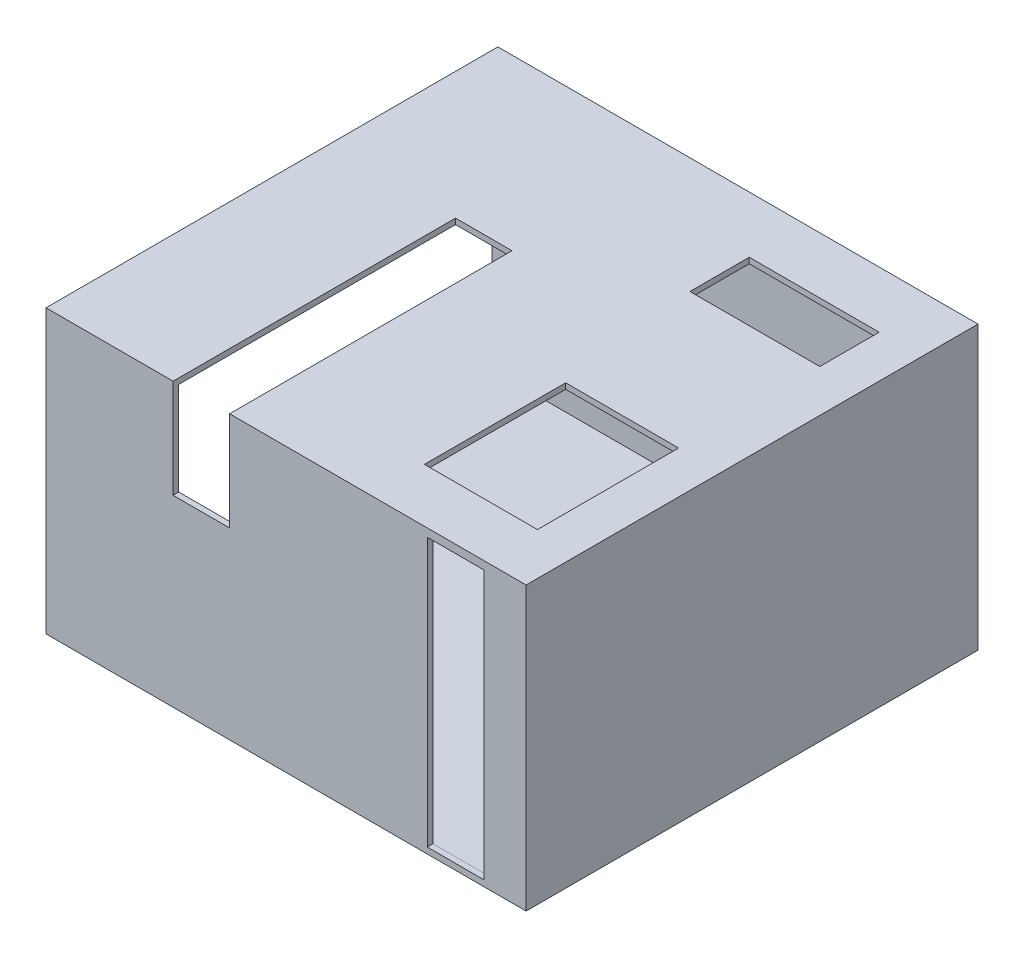
SolidWorks part; units mm, degrees
ref_plane "Front Plane" through (0, 0, 0) normal (0, 0, 1) x (1, 0, 0)
ref_plane "Top Plane" through (0, 0, 0) normal (0, 1, 0) x (1, 0, 0)
ref_plane "Right Plane" through (0, 0, 0) normal (1, 0, 0) x (0, 0, -1)
sketch "Sketch1" plane through (0, 0, 0) normal (0, 0, 1) x (1, 0, 0)
  line L2 (132.6799, -67.6565) -> (-67.3201, -67.6565)
  line L3 (132.6799, -67.6565) -> (132.6799, 32.3435)
  line L4 (132.6799, 32.3435) -> (-67.3201, 32.3435)
  line L5 (-67.3201, -67.6565) -> (-67.3201, 32.3435)
  dimension "D1" = 200
  dimension "D2" = 100
extrude "Boss-Extrude1" add sketch "Sketch1" along normal blind 160
shell "Shell3" thickness 2
sketch "Sketch2" plane through (0, 32.3435, 0) normal (0, 1, 0) x (1, 0, 0)
  line L0 (132.6799, -160) -> (132.6799, 0) construction
  line L1 (71.6799, -20) -> (117.6799, -20)
  line L2 (71.6799, -20) -> (71.6799, -41)
  line L3 (71.6799, -41) -> (117.6799, -41)
  line L4 (117.6799, -20) -> (117.6799, -41)
  line L5 (132.6799, 0) -> (-67.3201, 0) construction
  line L6 (77.6799, -91) -> (117.6799, -91)
  line L7 (77.6799, -91) -> (77.6799, -141)
  line L8 (77.6799, -141) -> (117.6799, -141)
  line L9 (117.6799, -91) -> (117.6799, -141)
  dimension "D1" = 46
  dimension "D2" = 21
  dimension "D3" = 15
  dimension "D4" = 40
  dimension "D5" = 50
  dimension "D6" = 20
  dimension "D7" = 50
extrude "Cut-Extrude1" cut sketch "Sketch2" against normal blind 68
sketch "Sketch4" plane through (0, 0, 160) normal (0, 0, 1) x (1, 0, 0)
  line L0 (132.6799, -67.6565) -> (132.6799, 32.3435) construction
  line L1 (97.6799, 29.4878) -> (117.6799, 29.4878)
  line L2 (97.6799, 29.4878) -> (97.6799, -65.5122)
  line L3 (97.6799, -65.5122) -> (117.6799, -65.5122)
  line L4 (117.6799, 29.4878) -> (117.6799, -65.5122)
  dimension "D1" = 20
  dimension "D2" = 95
  dimension "D3" = 15
extrude "Cut-Extrude2" cut sketch "Sketch4" against normal blind 18
sketch "Sketch6" plane through (0, 32.3435, 0) normal (0, 1, 0) x (1, 0, 0)
  line L0 (132.6799, -160) -> (-67.3201, -160) construction
  line L1 (7.6799, -60) -> (27.6799, -60)
  line L2 (7.6799, -60) -> (7.6799, -160)
  line L3 (7.6799, -160) -> (27.6799, -160)
  line L4 (27.6799, -60) -> (27.6799, -160)
  line L5 (77.6799, -91) -> (77.6799, -141) construction
  dimension "D1" = 20
  dimension "D2" = 100
  dimension "D3" = 50
extrude "Cut-Extrude3" cut sketch "Sketch6" against normal blind 35
ref_plane "Plane4" through (-67.3201, 0, 0) normal (-1, 0, 0) x (0, 0, 1)
sketch "Sketch8" plane through (-67.3201, 0, 0) normal (-1, 0, 0) x (0, 0, 1)
  line L1 (-4.5948, 34.539) -> (163.2423, 34.539)
  line L2 (-4.5948, 34.539) -> (-4.5948, -70.8357)
  line L3 (-4.5948, -70.8357) -> (163.2423, -70.8357)
  line L4 (163.2423, 34.539) -> (163.2423, -70.8357)
extrude "Cut-Extrude4" cut sketch "Sketch8" against normal blind 30
